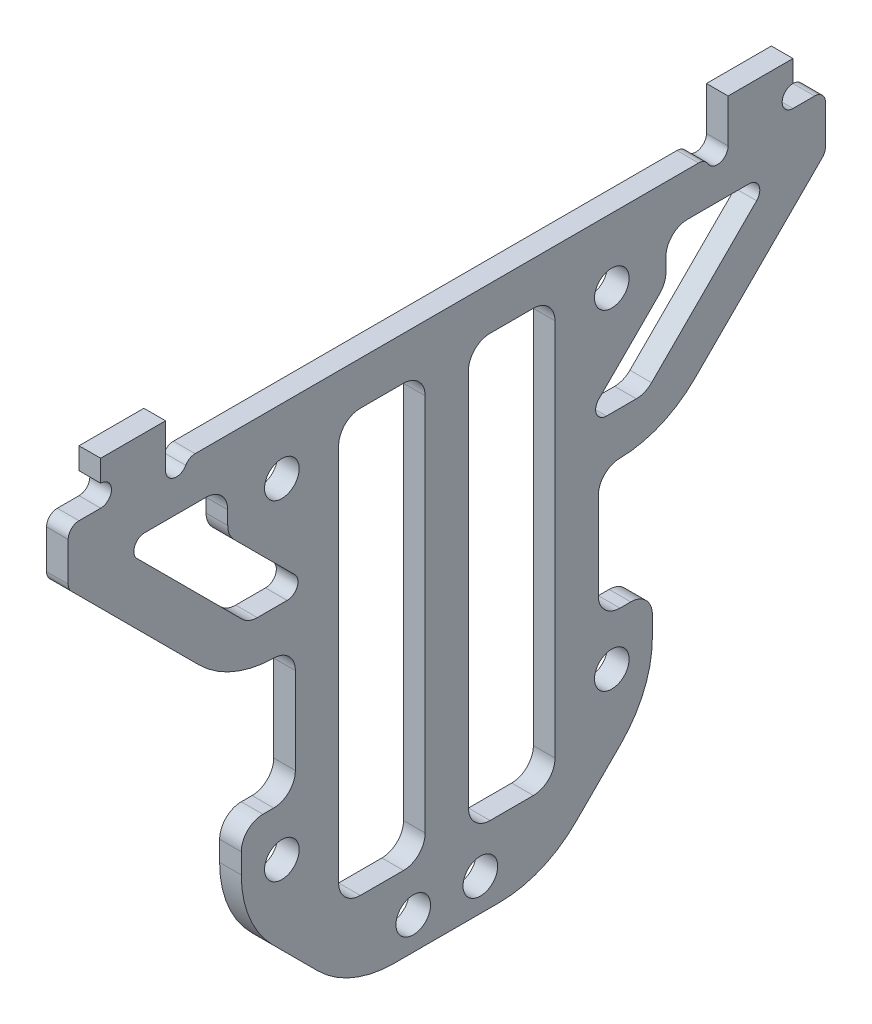
SolidWorks part; units mm, degrees
material "Thornel Mat VMA"
ref_plane "前视基准面" through (0, 0, 0) normal (0, 0, 1) x (1, 0, 0)
ref_plane "上视基准面" through (0, 0, 0) normal (0, 1, 0) x (1, 0, 0)
ref_plane "右视基准面" through (0, 0, 0) normal (1, 0, 0) x (0, 0, -1)
sketch "草图1" plane through (0, 0, 0) normal (1, 0, 0) x (0, 0, -1)
  line L0 (0, 0) -> (0, 19.099) construction
  line L1 (0, 50) -> (26, 50)
  line L2 (26, 50) -> (26, 54)
  line L3 (26, 54) -> (32, 54)
  line L4 (32, 54) -> (32, 50)
  line L5 (32, 50) -> (35, 50)
  line L6 (35, 50) -> (35, 30)
  line L7 (35, 30) -> (14, 30)
  line L8 (14, 30) -> (14, 18)
  line L10 (0, 0) -> (0, 50)
  line L12 (19, 0) -> (19, 18)
  line L13 (19, 18) -> (14, 18)
  line L14 (19, 0) -> (0, 0)
  dimension "D1" = 6
  dimension "D2" = 26
  dimension "D3" = 4
  dimension "D4" = 20
  dimension "D5" = 19
  dimension "D6" = 14
  dimension "D7" = 3
  dimension "D8" = 50
  dimension "D9" = 32
extrude "凸台-拉伸1" add sketch "草图1" along normal blind 2
mirror "镜向1" about plane through (2, 0, 0) normal (0, 0, -1) of "凸台-拉伸1"
hole_wizard "M3 间隙孔1" positions "草图2" profile "草图3" hole size "M3" standard "GB" end condition through all
sketch "草图2" plane through (2, 0, 0) normal (1, 0, 0) x (0, 0, -1)
  line L0 (0, 0) -> (0, 50) construction
  line L1 (26, 50) -> (-26, 50) construction
  point P0 (-15.25, 44)
  point P10 (-15.25, 13.5)
  point P13 (15.25, 13.5)
  point P14 (15.25, 44)
  dimension "D1" = 15.25
  dimension "D2" = 30.5
  dimension "D3" = 6
sketch "草图3" plane through (2, 44, 15.25) normal (0, 1, 0) x (0, 0, -1)
  line L0 (0, 0) -> (0, 2)
  line L1 (0, 2) -> (1.6, 2)
  line L2 (1.6, 2) -> (1.6, 0)
  line L5 (1.6, 0) -> (0, 0)
  line L11 (0, -6.35) -> (0, 107.95) construction
  dimension "通孔孔直径" = 3.2
  dimension "通孔孔深度" = 2
hole_wizard "M3 间隙孔2" positions "草图4" profile "草图5" hole size "M3" standard "GB" end condition through all
sketch "草图4" plane through (2, 0, 0) normal (1, 0, 0) x (0, 0, -1)
  line L4 (0, 0) -> (0, 50) construction
  line L5 (26, 50) -> (-26, 50) construction
  point P0 (-3.1, 3)
  point P22 (3.1, 3)
  dimension "D1" = 3.1
  dimension "D2" = 3
sketch "草图5" plane through (2, 3, 3.1) normal (0, 1, 0) x (0, 0, -1)
  line L0 (0, 0) -> (0, 2)
  line L1 (0, 2) -> (1.6, 2)
  line L2 (1.6, 2) -> (1.6, 0)
  line L5 (1.6, 0) -> (0, 0)
  line L11 (0, -6.35) -> (0, 107.95) construction
  dimension "通孔孔直径" = 3.2
  dimension "通孔孔深度" = 2
chamfer "倒角1" distance 15 angle 45 2 edges at (1, 30, -35) (1, 30, 35)
fillet "圆角1" radius 2 6 edges at (1, 30, -14) (1, 18, -14) (1, 18, -19) (1, 18, 19) (1, 18, 14) (1, 30, 14)
chamfer "倒角2" distance 10 angle 45 2 edges at (1, 0, -19) (1, 0, 19)
sketch "草图7" plane through (2, 0, 0) normal (1, 0, 0) x (0, 0, -1)
  line L0 (-30.3431, 46) -> (-18.3431, 34)
  line L1 (-18.3431, 34) -> (-16.3431, 34)
  line L2 (-16.3431, 34) -> (-10, 27.6569)
  line L4 (12.511, 9.1679) -> (-17.3211, 39)
  line L5 (-17.3211, 39) -> (-20.25, 39)
  line L6 (-35, 45) -> (-20, 30) construction
  line L7 (-20.25, 39) -> (-20.25, 46)
  line L8 (-20.25, 46) -> (-30.3431, 46)
  line L9 (0, 0) -> (0, 50) construction
  line L10 (26, 50) -> (-26, 50) construction
  line L11 (-10, 27.6569) -> (-10, 23.1711)
  line L12 (-10, 23.1711) -> (8.2571, 4.914)
  line L13 (8.2571, 4.914) -> (12.511, 9.1679)
  line L14 (-16, 30) -> (-20, 30) construction
  line L15 (-14, 20) -> (-14, 28) construction
  line L17 (9, 0) -> (19, 10) construction
  line L18 (-8.2571, 4.914) -> (-12.511, 9.1679)
  line L19 (10, 23.1711) -> (-8.2571, 4.914)
  line L20 (10, 27.6569) -> (10, 23.1711)
  line L21 (20.25, 46) -> (30.3431, 46)
  line L22 (20.25, 39) -> (20.25, 46)
  line L23 (17.3211, 39) -> (20.25, 39)
  line L24 (-12.511, 9.1679) -> (17.3211, 39)
  line L25 (16.3431, 34) -> (10, 27.6569)
  line L26 (18.3431, 34) -> (16.3431, 34)
  line L27 (30.3431, 46) -> (18.3431, 34)
  circle A0 centre (3.1, 3) radius 1.6 construction
  circle A2 centre (15.25, 13.5) radius 1.6 construction
  arc A3 (-14, 28) -> (-16, 30) centre (-16, 28) ccw construction
  circle A4 centre (-15.25, 44) radius 1.6 construction
  dimension "D5" = 5
  dimension "D6" = 4
  dimension "D1" = 4
  dimension "D2" = 4
  dimension "D3" = 4
  dimension "D4" = 5
  dimension "D7" = 5
  dimension "D8" = 4
  dimension "D9" = 5
  dimension "D10" = 4
sketch "草图6" plane through (2, 0, 0) normal (1, 0, 0) x (0, 0, -1)
  line L0 (0, 0) -> (0, 50) construction
  line L1 (26, 50) -> (-26, 50) construction
  line L2 (-14, 20) -> (-14, 28) construction
  line L3 (-10, 46) -> (-2, 46)
  line L4 (-10, 46) -> (-10, 7)
  line L5 (-10, 7) -> (-2, 7)
  line L6 (-2, 46) -> (-2, 7)
  line L7 (-30.3431, 46) -> (-18.3431, 34)
  line L8 (-18.3431, 34) -> (-12.3431, 34)
  line L9 (-12.3431, 34) -> (-20.25, 41.9069)
  line L10 (-24.3431, 46) -> (-30.3431, 46)
  line L11 (-35, 45) -> (-20, 30) construction
  line L12 (-20.25, 41.9069) -> (-20.25, 46)
  line L13 (-20.25, 46) -> (-24.3431, 46)
  line L15 (-16, 30) -> (-20, 30) construction
  circle A0 centre (-3.1, 3) radius 1.6 construction
  circle A1 centre (-15.25, 44) radius 1.6 construction
  dimension "D9" = 5
  dimension "D1" = 4
  dimension "D2" = 4
  dimension "D3" = 4
  dimension "D4" = 2
  dimension "D5" = 4
  dimension "D6" = 4
  dimension "D7" = 4
  dimension "D8" = 6
extrude "切除-拉伸1" cut sketch "草图6" against normal blind 100
fillet "圆角2" radius 1 2 edges at (1, 46, 30.3431) (1, 34, 12.3431)
fillet "圆角3" radius 2 7 edges at (1, 34, 18.3431) (1, 46, 20.25) (1, 41.9069, 20.25) (1, 7, 2) (1, 7, 10) (1, 46, 2) (1, 46, 10)
mirror "镜向2" about plane through (0, 0, 0) normal (0, 0, 1) of "圆角2", "圆角3", "切除-拉伸1"
sketch "草图8" plane through (2, 0, 0) normal (1, 0, 0) x (0, 0, -1)
  line L0 (26, 50) -> (-26, 50) construction
  line L1 (-32, 50) -> (-32, 54) construction
  line L2 (-35, 50) -> (-32, 50) construction
  line L3 (0, 50) -> (0, 62.7809) construction
  circle A0 centre (-25, 50) radius 1
  circle A1 centre (-32, 51) radius 1
  circle A2 centre (32, 51) radius 1
  circle A3 centre (25, 50) radius 1
  dimension "D1" = 2
  dimension "D2" = 2
extrude "切除-拉伸2" cut sketch "草图8" against normal blind 10
fillet "圆角4" radius 1 2 edges at (1, 50, -24) (1, 50, 24)
fillet "圆角5" radius 10 6 edges at (1, 30, -20) (1, 10, -19) (1, 0, -9) (1, 30, 20) (1, 10, 19) (1, 0, 9)
fillet "圆角6" radius 1 4 edges at (1, 45, -35) (1, 50, -35) (1, 45, 35) (1, 50, 35)
